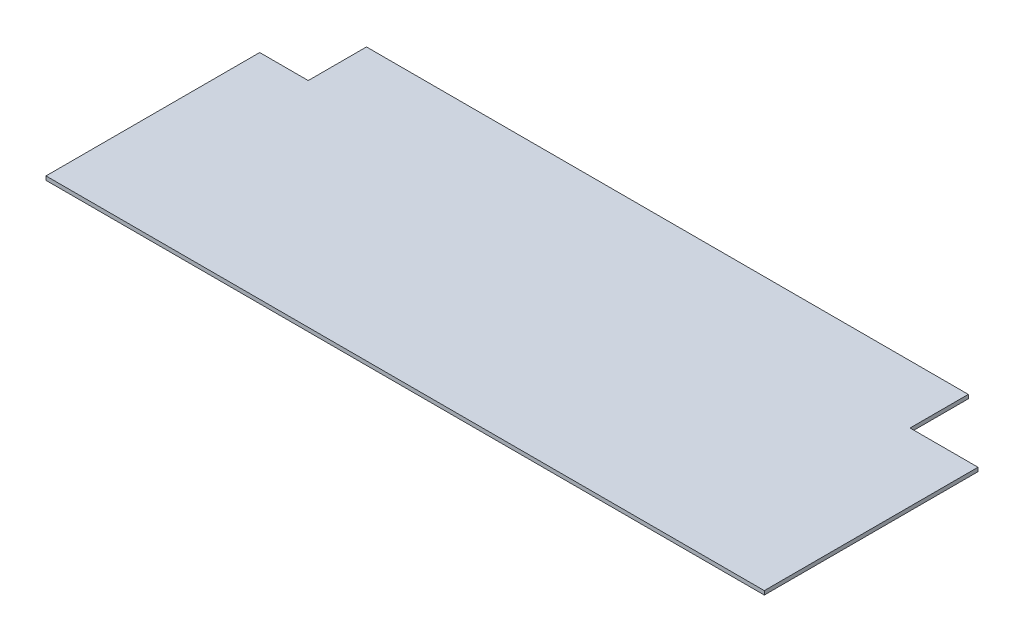
SolidWorks part; units mm, degrees
ref_plane "Front Plane" through (0, 0, 0) normal (0, 0, 1) x (1, 0, 0)
ref_plane "Top Plane" through (0, 0, 0) normal (0, 1, 0) x (1, 0, 0)
ref_plane "Right Plane" through (0, 0, 0) normal (1, 0, 0) x (0, 0, -1)
sketch "Sketch1" plane through (0, 0, 0) normal (0, 1, 0) x (1, 0, 0)
  line L0 (-130.625, 184.7613) -> (351.9808, 184.7613) construction
  line L1 (-124.2728, 0.5153) -> (345.6286, 0.5153)
  line L2 (-124.2728, 0.5153) -> (-124.2728, 178.4113)
  line L3 (-124.2728, 178.4113) -> (345.6286, 178.4113)
  line L4 (345.6286, 0.5153) -> (345.6286, 178.4113)
  line L13 (-124.2728, 178.4113) -> (-92.5228, 178.4113)
  line L14 (-124.2728, 178.4113) -> (-124.2728, 140.3113)
  line L15 (-124.2728, 140.3113) -> (-92.5228, 140.3113)
  line L16 (-92.5228, 178.4113) -> (-92.5228, 140.3113)
  line L17 (345.6286, 178.4113) -> (301.1786, 178.4113)
  line L18 (345.6286, 178.4113) -> (345.6286, 140.3113)
  line L19 (345.6286, 140.3113) -> (301.1786, 140.3113)
  line L20 (301.1786, 178.4113) -> (301.1786, 140.3113)
  line L21 (351.9786, 184.7613) -> (351.9786, -3.4747) construction
  line L22 (351.9808, -5.8347) -> (-130.625, -5.8347) construction
  line L23 (-130.6228, -5.8347) -> (-130.6228, 184.7613) construction
  dimension "D1" = 6.35
  dimension "D2" = 476.2514
  dimension "D3" = 6.35
  dimension "D4" = 6.35
  dimension "D5" = 6.35
  dimension "D6" = 38.1
  dimension "D7" = 31.75
  dimension "D8" = 44.45
extrude "Boss-Extrude1" add sketch "Sketch1" along normal blind 2.54 contours L1 L20 L19 L4 L3 L2 L15 L16
